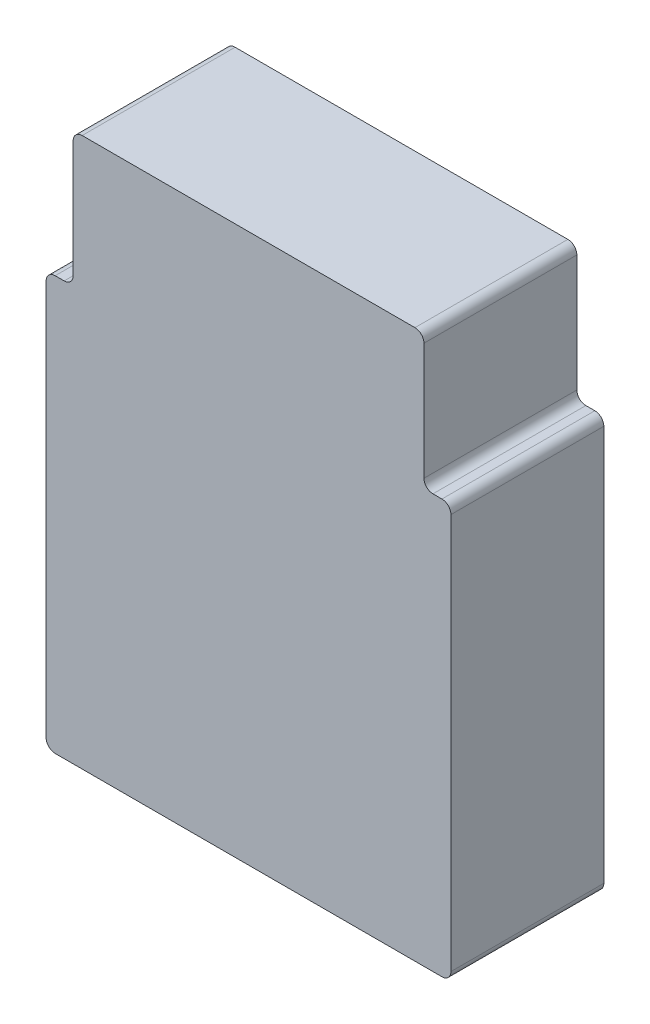
SolidWorks part; units mm, degrees
material "ABS PC"
ref_plane "前视基准面" through (0, 0, 0) normal (0, 0, 1) x (1, 0, 0)
ref_plane "上视基准面" through (0, 0, 0) normal (0, 1, 0) x (1, 0, 0)
ref_plane "右视基准面" through (0, 0, 0) normal (1, 0, 0) x (0, 0, -1)
other "Configuration Table"
sketch "草图1" plane through (0, 0, 0) normal (0, 0, 1) x (1, 0, 0)
  line L1 (-1.95, 0.75) -> (1.95, 0.75)
  line L2 (-1.95, 0.75) -> (-1.95, -0.75)
  line L3 (-1.95, -0.75) -> (1.95, -0.75)
  line L4 (1.95, 0.75) -> (1.95, -0.75)
  line L5 (0, -0.75) -> (0, 0.75) construction
  line L6 (-1.95, 0) -> (1.95, 0) construction
  line L7 (-2.25, -5.35) -> (2.25, -5.35)
  line L8 (-2.25, -5.35) -> (-2.25, -0.75)
  line L9 (-2.25, -0.75) -> (2.25, -0.75)
  line L10 (2.25, -5.35) -> (2.25, -0.75)
  line L11 (0, -0.75) -> (0, -5.35) construction
  line L12 (-2.25, -3.05) -> (2.25, -3.05) construction
  point P0 (0, 0)
  point P4 (0, -3.05)
  dimension "D1" = 4.5
  dimension "D2" = 3.9
  dimension "D3" = 1.5
  dimension "D4" = 6.1
extrude "凸台-拉伸1" add sketch "草图1" along normal mid plane 1.7 contours L4 L1 L2 L3 | L7 L10 L9 L3 L8
fillet "圆角1" radius 0.1 8 edges at (1.95, -0.75, 0) (2.25, -0.75, 0) (2.25, -5.35, 0) (-2.25, -5.35, 0) (-2.25, -0.75, 0) (-1.95, -0.75, 0) (-1.95, 0.75, 0) (1.95, 0.75, 0)
